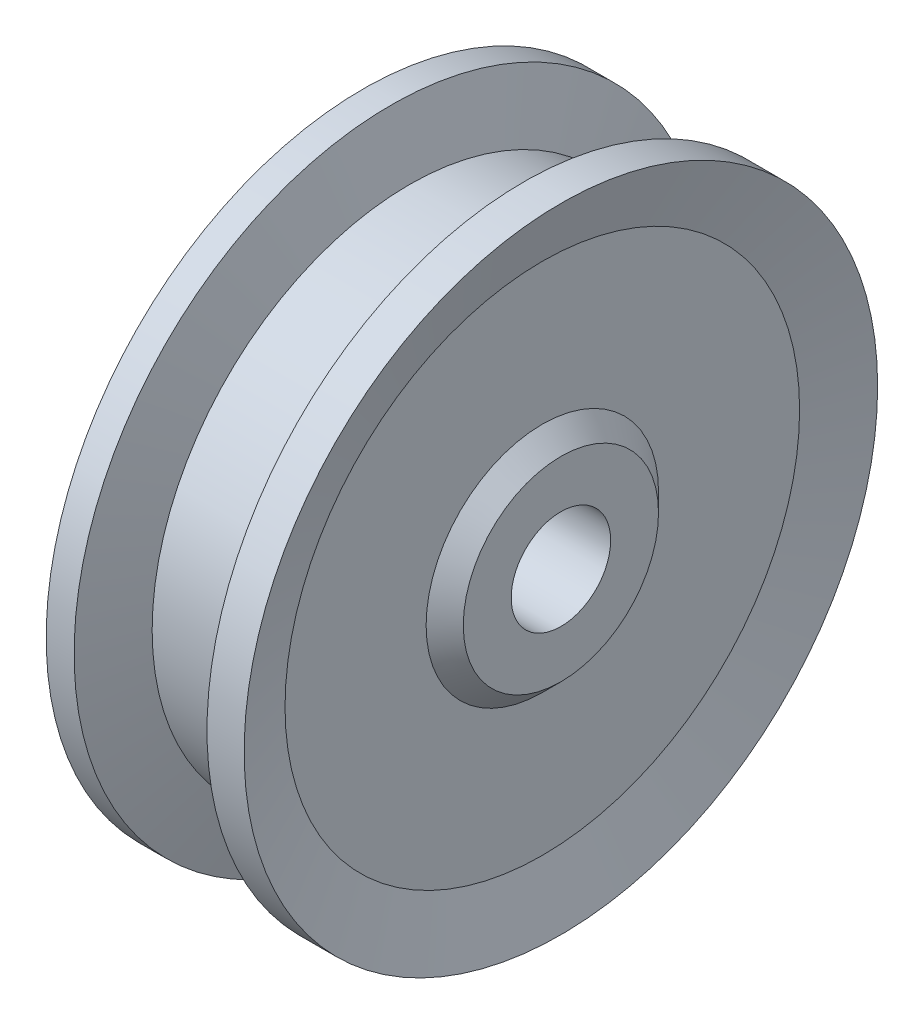
SolidWorks part; units mm, degrees
ref_plane "Alzado" through (0, 0, 0) normal (0, 0, 1) x (1, 0, 0)
ref_plane "Planta" through (0, 0, 0) normal (0, 1, 0) x (1, 0, 0)
ref_plane "Vista lateral" through (0, 0, 0) normal (1, 0, 0) x (0, 0, -1)
sketch "Croquis1" plane through (0, 0, 0) normal (0, 0, 1) x (1, 0, 0)
  line L0 (57.6768, 0) -> (-57.6768, 0) construction
  line L1 (-12.5, 6.2808) -> (12.5, 6.2808)
  line L2 (-12.5, -40) -> (12.5, -40) construction
  line L3 (-12.5, -40) -> (-12.5, 40) construction
  line L4 (-12.5, 40) -> (12.5, 40) construction
  line L5 (12.5, -40) -> (12.5, 40) construction
  line L6 (-12.5, -40) -> (12.5, 40) construction
  line L7 (-12.5, 40) -> (12.5, -40) construction
  line L8 (12.5, 6.2808) -> (12.5, 12.3274)
  line L9 (12.5, 12.3274) -> (10.1534, 14.674)
  line L10 (10.1534, 14.674) -> (10.1534, 32.4908)
  line L11 (10.1534, 32.4908) -> (12.5, 40)
  line L12 (12.5, 40) -> (7.8067, 40)
  line L13 (7.8067, 40) -> (5.4601, 32.4908)
  line L14 (5.4601, 32.4908) -> (-6.6271, 32.4908)
  line L15 (-6.6271, 32.4908) -> (-8.9737, 40)
  line L16 (-8.9737, 40) -> (-12.5, 40)
  line L17 (-12.5, 40) -> (-10.1534, 32.4908)
  line L18 (-10.1534, 32.4908) -> (-10.1534, 14.674)
  line L19 (-10.1534, 14.674) -> (-12.5, 12.3274)
  line L20 (-12.5, 12.3274) -> (-12.5, 6.2808)
  point P0 (0, 0)
  point P4 (0, 0)
  point P11 (-13.844, 40)
  dimension "D1" = 80
  dimension "D2" = 25
revolve "Revolución1" add sketch "Croquis1" angle 360 about L0
sketch "Croquis2" plane through (0, 0, 0) normal (1, 0, 0) x (0, 0, -1)
  circle A0 centre (0, 0) radius 37.5474
